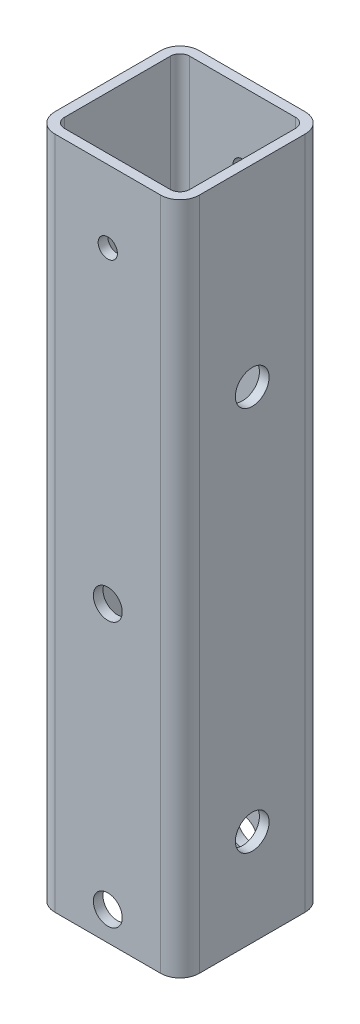
SolidWorks part; units mm, degrees
material "AISI 1010 钢，热轧条材"
ref_plane "前视基准面" through (0, 0, 0) normal (0, 0, 1) x (1, 0, 0)
ref_plane "上视基准面" through (0, 0, 0) normal (0, 1, 0) x (1, 0, 0)
ref_plane "右视基准面" through (0, 0, 0) normal (1, 0, 0) x (0, 0, -1)
sketch "草图2" plane through (0, 0, 0) normal (0, 1, 0) x (1, 0, 0)
  line L0 (4, 2) -> (26, 2)
  line L1 (4, 0) -> (26, 0)
  line L2 (0, 4) -> (0, 26)
  line L3 (4, 30) -> (26, 30)
  line L4 (30, 4) -> (30, 26)
  line L5 (28, 4) -> (28, 26)
  line L6 (4, 28) -> (26, 28)
  line L7 (2, 4) -> (2, 26)
  arc A0 (4, 0) -> (0, 4) centre (4, 4) cw
  arc A1 (26, 0) -> (30, 4) centre (26, 4) ccw
  arc A2 (26, 30) -> (30, 26) centre (26, 26) cw
  arc A3 (0, 26) -> (4, 30) centre (4, 26) cw
  arc A4 (26, 2) -> (28, 4) centre (26, 4) ccw
  arc A5 (26, 28) -> (28, 26) centre (26, 26) cw
  arc A6 (2, 26) -> (4, 28) centre (4, 26) cw
  arc A7 (4, 2) -> (2, 4) centre (4, 4) cw
  point P7 (0, 0)
  point P10 (30, 0)
  point P13 (30, 30)
  point P16 (0, 30)
  dimension "D3" = 4
  dimension "D1" = 30
  dimension "D2" = 30
  dimension "D4" = 2
extrude "凸台-拉伸1" add sketch "草图2" along normal mid plane 140
sketch "草图3" plane through (0, 0, 0) normal (0, 0, 1) x (1, 0, 0)
  line L0 (4, -70) -> (26, -70) construction
  line L1 (4, 70) -> (26, 70) construction
  circle A0 centre (15, -64) radius 3
  circle A1 centre (15, -9) radius 3
  circle A2 centre (15, 55) radius 2
  point P7 (15, -70)
  dimension "D1" = 6
  dimension "D4" = 4
  dimension "D2" = 6
  dimension "D3" = 55
  dimension "D5" = 15
extrude "切除-拉伸1" cut sketch "草图3" against normal through all
sketch "草图4" plane through (0, 0, 0) normal (1, 0, 0) x (0, 0, -1)
  line L0 (4, -70) -> (26, -70) construction
  line L1 (0, 70) -> (0, -70) construction
  circle A0 centre (15, -50) radius 3.5
  circle A1 centre (15, 30) radius 3.5
  dimension "D4" = 7
  dimension "D1" = 20
  dimension "D2" = 80
  dimension "D3" = 15
extrude "切除-拉伸2" cut sketch "草图4" along normal through all and the other way through all
